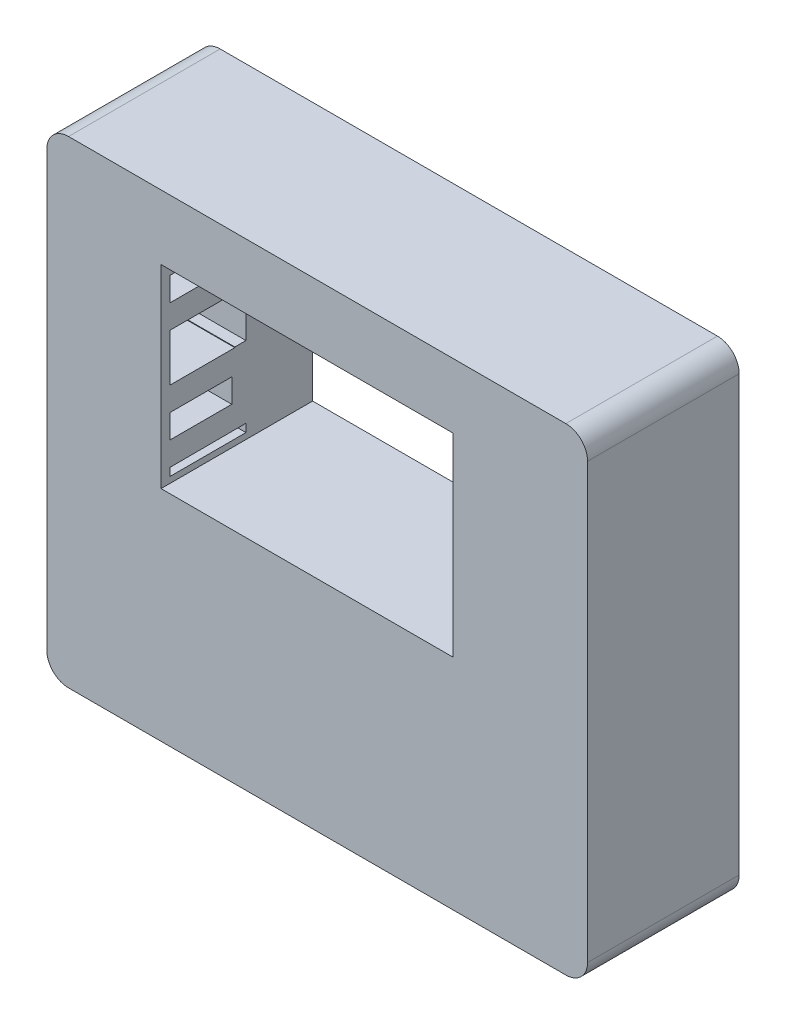
SolidWorks part; units mm, degrees
ref_plane "Front Plane" through (0, 0, 0) normal (0, 0, 1) x (1, 0, 0)
ref_plane "Top Plane" through (0, 0, 0) normal (0, 1, 0) x (1, 0, 0)
ref_plane "Right Plane" through (0, 0, 0) normal (1, 0, 0) x (0, 0, -1)
sketch "Sketch1" plane through (0, 0, 0) normal (0, 0, 1) x (1, 0, 0)
  line L0 (84, 51.09) -> (-14.4, 51.09) construction
  line L1 (-18.7, 46.79) -> (-18.7, -39.11) construction
  line L2 (-14.4, -43.41) -> (84, -43.41) construction
  line L3 (88.3, -39.11) -> (88.3, 46.79) construction
  line L4 (61.7, -0.1) -> (61.7, 38.3) construction
  line L5 (61.7, 38.3) -> (3.9, 38.3) construction
  line L6 (3.9, 38.3) -> (3.9, -0.1) construction
  line L7 (3.9, -0.1) -> (61.7, -0.1) construction
  line L8 (84, 51.09) -> (-14.4, 51.09)
  line L9 (-18.7, 46.79) -> (-18.7, -39.11)
  line L10 (-14.4, -43.41) -> (84, -43.41)
  line L11 (88.3, -39.11) -> (88.3, 46.79)
  line L12 (61.7, -0.1) -> (61.7, 38.3)
  line L13 (61.7, 38.3) -> (3.9, 38.3)
  line L14 (3.9, 38.3) -> (3.9, -0.1)
  line L15 (3.9, -0.1) -> (61.7, -0.1)
  arc A0 (88.3, 46.79) -> (84, 51.09) centre (84, 46.79) ccw construction
  arc A1 (-14.4, 51.09) -> (-18.7, 46.79) centre (-14.4, 46.79) ccw construction
  arc A2 (-18.7, -39.11) -> (-14.4, -43.41) centre (-14.4, -39.11) ccw construction
  arc A3 (84, -43.41) -> (88.3, -39.11) centre (84, -39.11) ccw construction
  arc A4 (88.3, 46.79) -> (84, 51.09) centre (84, 46.79) ccw
  arc A5 (-14.4, 51.09) -> (-18.7, 46.79) centre (-14.4, 46.79) ccw
  arc A6 (-18.7, -39.11) -> (-14.4, -43.41) centre (-14.4, -39.11) ccw
  arc A7 (84, -43.41) -> (88.3, -39.11) centre (84, -39.11) ccw
extrude "Boss-Extrude1" add sketch "Sketch1" against normal blind 30
sketch "Sketch2" plane through (0, -43.41, 0) normal (0, -1, 0) x (1, 0, 0)
  line L0 (72.33, -24.7898) -> (72.33, -28.2198) construction
  line L1 (72.33, -28.2198) -> (81.22, -28.2198) construction
  line L2 (81.22, -28.2198) -> (81.22, -24.7898) construction
  line L3 (81.22, -24.7898) -> (72.33, -24.7898) construction
  line L4 (66.12, -28.296) -> (68.12, -28.296) construction
  line L5 (68.12, -14.646) -> (66.12, -14.646) construction
  line L6 (68.12, -28.296) -> (69.827, -28.296) construction
  line L7 (69.827, -28.296) -> (69.827, -14.646) construction
  line L8 (69.827, -14.646) -> (68.12, -14.646) construction
  line L9 (57.38, -28.296) -> (66.12, -28.296) construction
  line L10 (66.12, -14.646) -> (57.38, -14.646) construction
  line L11 (55.38, -28.296) -> (57.38, -28.296) construction
  line L12 (57.38, -14.646) -> (55.38, -14.646) construction
  line L13 (53.673, -14.646) -> (53.673, -28.296) construction
  line L14 (53.673, -28.296) -> (55.38, -28.296) construction
  line L15 (55.38, -14.646) -> (53.673, -14.646) construction
  line L16 (37.375, -11.3798) -> (37.375, -28.2198) construction
  line L17 (37.375, -28.2198) -> (51.425, -28.2198) construction
  line L18 (51.425, -28.2198) -> (51.425, -11.3798) construction
  line L19 (51.425, -11.3798) -> (37.375, -11.3798) construction
  line L20 (20.375, -11.3798) -> (20.375, -28.2198) construction
  line L21 (20.375, -28.2198) -> (34.425, -28.2198) construction
  line L22 (34.425, -28.2198) -> (34.425, -11.3798) construction
  line L23 (34.425, -11.3798) -> (20.375, -11.3798) construction
  line L24 (-1.288, -21.4098) -> (-1.288, -28.2198) construction
  line L25 (-1.288, -28.2198) -> (16.408, -28.2198) construction
  line L26 (16.408, -28.2198) -> (16.408, -21.4098) construction
  line L27 (16.408, -21.4098) -> (-1.288, -21.4098) construction
  line L28 (-13.85, -17.296) -> (-13.85, -28.296) construction
  line L29 (-13.85, -28.296) -> (-4.55, -28.296) construction
  line L30 (-4.55, -28.296) -> (-4.55, -17.296) construction
  line L31 (-4.55, -17.296) -> (-13.85, -17.296) construction
  line L32 (72.33, -24.7898) -> (72.33, -28.2198)
  line L33 (72.33, -28.2198) -> (81.22, -28.2198)
  line L34 (81.22, -28.2198) -> (81.22, -24.7898)
  line L35 (81.22, -24.7898) -> (72.33, -24.7898)
  line L36 (66.12, -28.296) -> (68.12, -28.296)
  line L37 (68.12, -14.646) -> (66.12, -14.646)
  line L38 (68.12, -28.296) -> (69.827, -28.296)
  line L39 (69.827, -28.296) -> (69.827, -14.646)
  line L40 (69.827, -14.646) -> (68.12, -14.646)
  line L41 (57.38, -28.296) -> (66.12, -28.296)
  line L42 (66.12, -14.646) -> (57.38, -14.646)
  line L43 (55.38, -28.296) -> (57.38, -28.296)
  line L44 (57.38, -14.646) -> (55.38, -14.646)
  line L45 (53.673, -14.646) -> (53.673, -28.296)
  line L46 (53.673, -28.296) -> (55.38, -28.296)
  line L47 (55.38, -14.646) -> (53.673, -14.646)
  line L48 (37.375, -11.3798) -> (37.375, -28.2198)
  line L49 (37.375, -28.2198) -> (51.425, -28.2198)
  line L50 (51.425, -28.2198) -> (51.425, -11.3798)
  line L51 (51.425, -11.3798) -> (37.375, -11.3798)
  line L52 (20.375, -11.3798) -> (20.375, -28.2198)
  line L53 (20.375, -28.2198) -> (34.425, -28.2198)
  line L54 (34.425, -28.2198) -> (34.425, -11.3798)
  line L55 (34.425, -11.3798) -> (20.375, -11.3798)
  line L56 (-1.288, -21.4098) -> (-1.288, -28.2198)
  line L57 (-1.288, -28.2198) -> (16.408, -28.2198)
  line L58 (16.408, -28.2198) -> (16.408, -21.4098)
  line L59 (16.408, -21.4098) -> (-1.288, -21.4098)
  line L60 (-13.85, -17.296) -> (-13.85, -28.296)
  line L61 (-13.85, -28.296) -> (-4.55, -28.296)
  line L62 (-4.55, -28.296) -> (-4.55, -17.296)
  line L63 (-4.55, -17.296) -> (-13.85, -17.296)
extrude "Cut-Extrude1" cut sketch "Sketch2" against normal blind 23
sketch "Sketch3" plane through (-18.7, 0, 0) normal (-1, 0, 0) x (0, 0, 1)
  line L0 (-1.8, 35.55) -> (-14, 35.55)
  line L1 (-1.8, 34) -> (-1.8, 37.1) construction
  line L2 (-14, 37.1) -> (-14, 34) construction
  line L3 (-14, 35.55) -> (-14, 30.85)
  line L4 (-14, 32.4) -> (-14, 29.3) construction
  line L5 (-14, 30.85) -> (-1.8, 30.85)
  line L6 (-1.8, 29.3) -> (-1.8, 32.4) construction
  line L7 (-1.8, 30.85) -> (-1.8, 35.55)
  line L8 (-16.8, 26.15) -> (-1.8, 26.15)
  line L9 (-1.8, 24.6) -> (-1.8, 27.7) construction
  line L10 (-1.8, 26.15) -> (-1.8, 16.75)
  line L11 (-1.8, 15.2) -> (-1.8, 18.3) construction
  line L12 (-14.6, 5.8) -> (-16.8, 5.8)
  line L13 (-16.8, 5.8) -> (-16.8, -0.4)
  line L14 (-16.8, -0.4) -> (-0.3, -0.4)
  line L15 (0, -0.1) -> (0, 38.3)
  line L16 (-0.3, 38.6) -> (-16.8, 38.6)
  line L17 (-16.8, 38.6) -> (-16.8, 36.42)
  line L18 (-16.8, 36.42) -> (-16.6, 36.42)
  line L19 (-16.6, 36.42) -> (-16.6, 30.32)
  line L20 (-16.6, 30.32) -> (-16.8, 30.32)
  line L21 (-16.8, 30.32) -> (-16.8, 16.875)
  line L22 (-16.8, 16.875) -> (-14.6, 16.875)
  line L23 (-14.6, 16.875) -> (-14.6, 5.8)
  line L25 (-16.8, 2.7) -> (-16.8, 1.1)
  line L34 (-16.8, 16.875) -> (-14.6, 16.875)
  line L35 (-14.6, 16.875) -> (-14.6, 16.75)
  line L36 (-1.8, 16.75) -> (-14.6, 16.75)
  line L37 (-16.8, 26.15) -> (-16.8, 16.875)
  line L38 (-1.8, 12.05) -> (-14, 12.05)
  line L39 (-1.8, 10.5) -> (-1.8, 13.6) construction
  line L40 (-14, 13.6) -> (-14, 10.5) construction
  line L41 (-14, 12.05) -> (-14, 7.35)
  line L42 (-14, 8.9) -> (-14, 5.8) construction
  line L43 (-14, 7.35) -> (-1.8, 7.35)
  line L44 (-1.8, 7.35) -> (-1.8, 12.05)
  line L45 (-1.8, 2.65) -> (-16.8, 2.7)
  line L46 (-1.8, 1.1) -> (-1.8, 4.2) construction
  line L47 (-1.8, 2.65) -> (-1.8, 1.1)
  line L48 (-1.8, 1.1) -> (-16.8, 1.1)
  line L49 (-16.8, 1.1) -> (-16.8, 2.7)
  arc A2 (-0.3, -0.4) -> (0, -0.1) centre (-0.3, -0.1) ccw
  arc A3 (0, 38.3) -> (-0.3, 38.6) centre (-0.3, 38.3) ccw
  dimension "D1" = 0
extrude "Cut-Extrude2" cut sketch "Sketch3" against normal blind 23 contours L5 L7 L0 L3 | L8 L37 L34 L35 L36 L10 | L43 L44 L38 L41 | L48 L47 L45 L25
